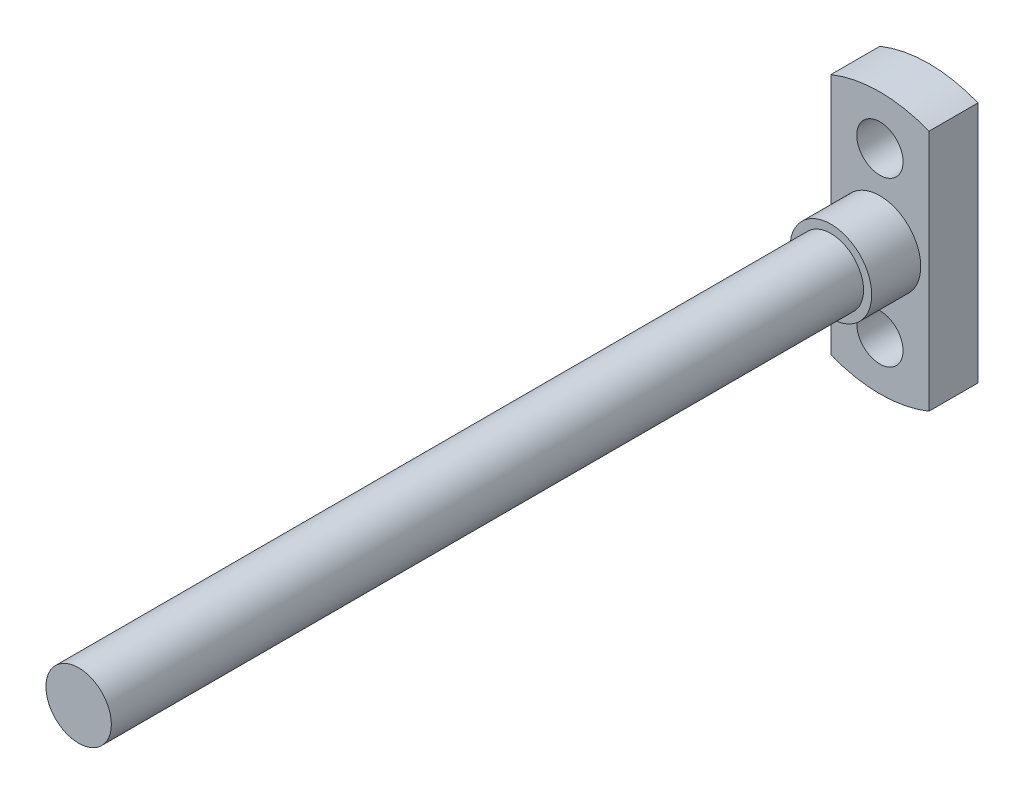
SolidWorks part; units mm, degrees
ref_plane "Front Plane" through (0, 0, 0) normal (0, 0, 1) x (1, 0, 0)
ref_plane "Top Plane" through (0, 0, 0) normal (0, 1, 0) x (1, 0, 0)
ref_plane "Right Plane" through (0, 0, 0) normal (1, 0, 0) x (0, 0, -1)
sketch "Sketch1" plane through (0, 0, 0) normal (0, 0, 1) x (1, 0, 0)
  line L0 (0, 0) -> (9.525, 23.5464) construction
  line L2 (0, 0) -> (0, 23.5464)
  line L4 (9.525, 0) -> (9.525, 23.5464)
  arc A0 (0, 23.5464) -> (9.525, 23.5464) centre (4.7625, 11.7732) cw
  arc A1 (9.525, 0) -> (0, 0) centre (4.7625, 11.7732) cw
  dimension "D1" = 12.7
  dimension "D2" = 9.525
extrude "Boss-Extrude1" add sketch "Sketch1" along normal blind 4.7625
sketch "Sketch2" plane through (0, 0, 4.7625) normal (0, 0, 1) x (1, 0, 0)
  line L0 (0, 23.5464) -> (9.525, 0) construction
  circle A0 centre (4.7625, 11.7732) radius 3.9688
  dimension "D1" = 7.9375
extrude "Boss-Extrude2" add sketch "Sketch2" along normal blind 4.7625
sketch "Sketch3" plane through (0, 0, 9.525) normal (0, 0, 1) x (1, 0, 0)
  circle A0 centre (4.7625, 11.7732) radius 3.175
  dimension "D1" = 6.35
extrude "Boss-Extrude3" add sketch "Sketch3" along normal blind 73.025
hole_wizard "#16 (0.177) Diameter Hole1" positions "Sketch5" profile "Sketch6" hole size "#16" standard "ANSI Inch" end condition through all
sketch "Sketch5" plane through (0, 0, 4.7625) normal (0, 0, 1) x (1, 0, 0)
  line L0 (4.7625, 24.4732) -> (4.7625, -0.9268) construction
  line L4 (0, 11.7732) -> (9.1829, 11.7732) construction
  line L5 (0, 23.5464) -> (0, 0) construction
  arc A1 (9.525, 23.5464) -> (0, 23.5464) centre (4.7625, 11.7732) ccw construction
  arc A2 (0, 0) -> (9.525, 0) centre (4.7625, 11.7732) ccw construction
  point P17 (4.7625, 3.8357)
  point P20 (4.7625, 19.7107)
  point P25 (0, 11.7732)
  dimension "D1" = 7.9375
sketch "Sketch6" plane through (4.7625, 3.8357, 4.7625) normal (1, 0, 0) x (0, -1, 0)
  line L0 (0, 0) -> (0, 4.7625)
  line L1 (0, 4.7625) -> (2.2479, 4.7625)
  line L2 (2.2479, 4.7625) -> (2.2479, 0)
  line L5 (2.2479, 0) -> (0, 0)
  line L11 (0, -6.35) -> (0, 107.95) construction
  dimension "Thru Hole Dia." = 4.4958
  dimension "Thru Hole Depth" = 4.7625
